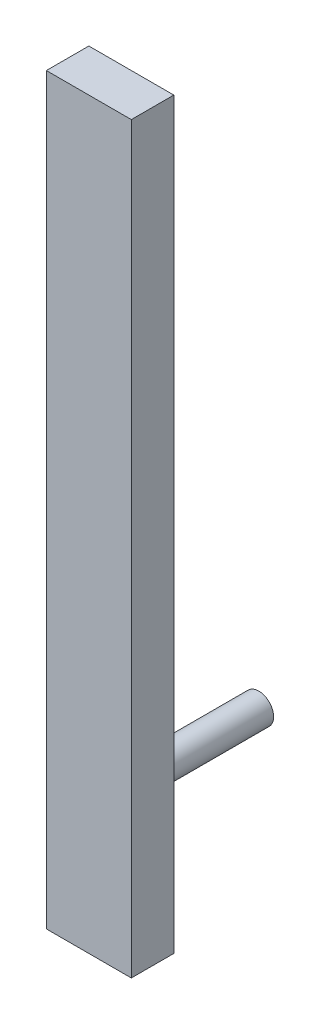
SolidWorks part; units mm, degrees
ref_plane "Front" through (0, 0, 0) normal (0, 0, 1) x (1, 0, 0)
ref_plane "Top" through (0, 0, 0) normal (0, 1, 0) x (1, 0, 0)
ref_plane "Right" through (0, 0, 0) normal (1, 0, 0) x (0, 0, -1)
sketch "Sketch1" plane through (0, 0, 0) normal (0, 0, 1) x (1, 0, 0)
  line L1 (161.3176, -60.5) -> (201.3176, -60.5)
  line L2 (161.3176, -60.5) -> (161.3176, 289.5)
  line L3 (161.3176, 289.5) -> (201.3176, 289.5)
  line L4 (201.3176, -60.5) -> (201.3176, 289.5)
  dimension "D2" = 40
  dimension "D3" = 350
extrude "Extrude1" add sketch "Sketch1" along normal blind 20
sketch "Sketch2" plane through (0, 0, 0) normal (0, 0, -1) x (-1, 0, 0)
  line L0 (-161.3176, -60.5) -> (-201.3176, -60.5) construction
  line L1 (-181.3176, -60.5) -> (-181.3176, 47.8764) construction
  circle A0 centre (-181.3176, -0.5) radius 7
  dimension "D1" = 14
  dimension "D2" = 60
extrude "Extrude2" add sketch "Sketch2" along normal blind 60
ref_plane "Plane1" through (181.3176, 0, 0) normal (1, 0, 0) x (0, 0, -1)
